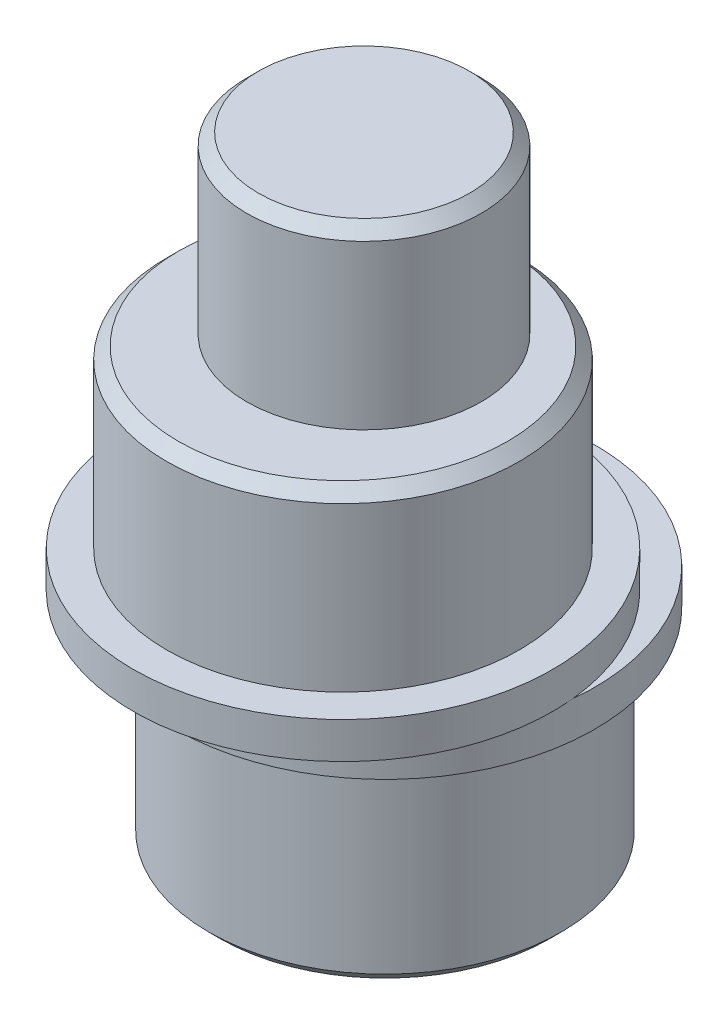
SolidWorks part; units mm, degrees
ref_plane "Front Plane" through (0, 0, 0) normal (0, 0, 1) x (1, 0, 0)
ref_plane "Top Plane" through (0, 0, 0) normal (0, 1, 0) x (1, 0, 0)
ref_plane "Right Plane" through (0, 0, 0) normal (1, 0, 0) x (0, 0, -1)
sketch "Sketch1" plane through (0, 0, 0) normal (0, 1, 0) x (1, 0, 0)
  circle A0 centre (0, 0.72) radius 6.05
  dimension "D1" = 12.1
  dimension "D2" = 0.72
extrude "Boss-Extrude1" add sketch "Sketch1" along normal blind 7
sketch "Sketch2" plane through (0, 7, 0) normal (0, 1, 0) x (1, 0, 0)
  circle A0 centre (0, 0.72) radius 7.2
  dimension "D1" = 14.4
extrude "Boss-Extrude2" add sketch "Sketch2" along normal blind 1.25
sketch "Sketch3" plane through (0, 8.25, 0) normal (0, 1, 0) x (1, 0, 0)
  circle A0 centre (0, -0.72) radius 7.2
  dimension "D1" = 14.4
  dimension "D2" = 0.72
extrude "Boss-Extrude3" add sketch "Sketch3" along normal blind 1.25
sketch "Sketch4" plane through (0, 9.5, 0) normal (0, 1, 0) x (1, 0, 0)
  circle A0 centre (0, -0.72) radius 6.05
  dimension "D1" = 12.1
  dimension "D2" = 0.72
extrude "Boss-Extrude4" add sketch "Sketch4" along normal blind 6
sketch "Sketch5" plane through (0, 0, 0) normal (0, -1, 0) x (1, 0, 0)
  line L0 (0, 0) -> (0, 2.15) construction
  line L1 (1.506, 2.15) -> (-1.506, 2.15)
  arc A0 (-1.506, 2.15) -> (1.506, 2.15) centre (0, 0) ccw
  point P7 (0, 2.15)
  dimension "D1" = 5.25
  dimension "D2" = 2.15
extrude "Cut-Extrude2" cut sketch "Sketch5" against normal blind 11 and the other way through all
sketch "Sketch6" plane through (0, 15.5, 0) normal (0, 1, 0) x (1, 0, 0)
  circle A0 centre (0, 0) radius 4.025
  dimension "D1" = 8.05
extrude "Boss-Extrude5" add sketch "Sketch6" along normal blind 6
sketch "Sketch7" plane through (0, 15.5, 0) normal (0, 1, 0) x (1, 0, 0)
  line L0 (0, 5.33) -> (0, -6.77) construction
  circle A0 centre (0, -0.72) radius 6.05 construction
  circle A1 centre (0, -0.72) radius 6.05 construction
chamfer "Chamfer1" distance 0.4 angle 45 1 edges at (0, 21.5, 4.025)
chamfer "Chamfer2" distance 0.4 angle 45 2 edges at (0, 15.5, 6.77) (0, 0, 5.33)
